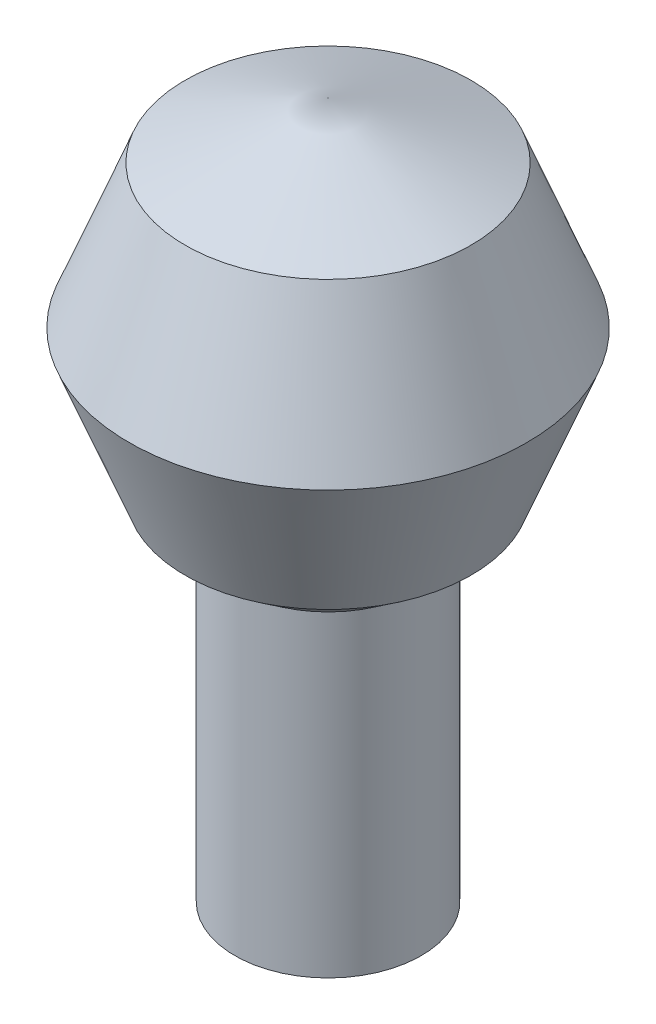
SolidWorks part; units mm, degrees
material "AISI 304"
ref_plane "Alzado" through (0, 0, 0) normal (0, 0, 1) x (1, 0, 0)
ref_plane "Planta" through (0, 0, 0) normal (0, 1, 0) x (1, 0, 0)
ref_plane "Vista lateral" through (0, 0, 0) normal (1, 0, 0) x (0, 0, -1)
sketch "Sketch1" plane through (0, 0, 0) normal (0, 0, 1) x (1, 0, 0)
  line L0 (0, 3.2) -> (2.3, 2.3)
  line L1 (2.3, 2.3) -> (3.2, 0)
  line L2 (3.2, 0) -> (2.3, -2.3)
  line L3 (2.3, -2.3) -> (1.5, -2.9)
  line L4 (1.5, -2.9) -> (1.5, -8)
  line L5 (1.5, -8) -> (0, -8)
  line L6 (0, -8) -> (0, 3.2)
  line L7 (0, -12) -> (0, 7.2) construction
revolve "Ancla_de_insercion" add sketch "Sketch1" angle 360 about L7
